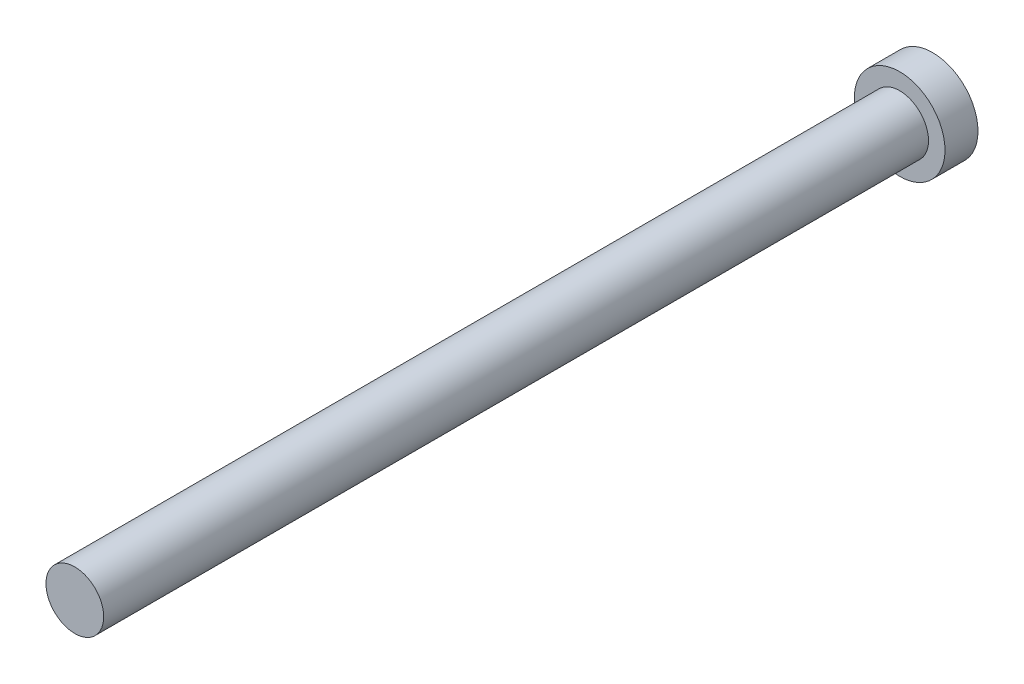
SolidWorks part; units mm, degrees
ref_plane "前基準面" through (0, 0, 0) normal (0, 0, 1) x (1, 0, 0)
ref_plane "上基準面" through (0, 0, 0) normal (0, 1, 0) x (1, 0, 0)
ref_plane "右基準面" through (0, 0, 0) normal (1, 0, 0) x (0, 0, -1)
sketch "草圖1" plane through (0, 0, 0) normal (0, 0, 1) x (1, 0, 0)
  circle A0 centre (0, 0) radius 2.75
  dimension "D1" = 5.5
extrude "伸長1" add sketch "草圖1" along normal blind 2
sketch "草圖2" plane through (0, 0, 2) normal (0, 0, 1) x (1, 0, 0)
  circle A0 centre (0, 0) radius 1.75
  dimension "D1" = 3.5
extrude "伸長2" add sketch "草圖2" along normal blind 50
